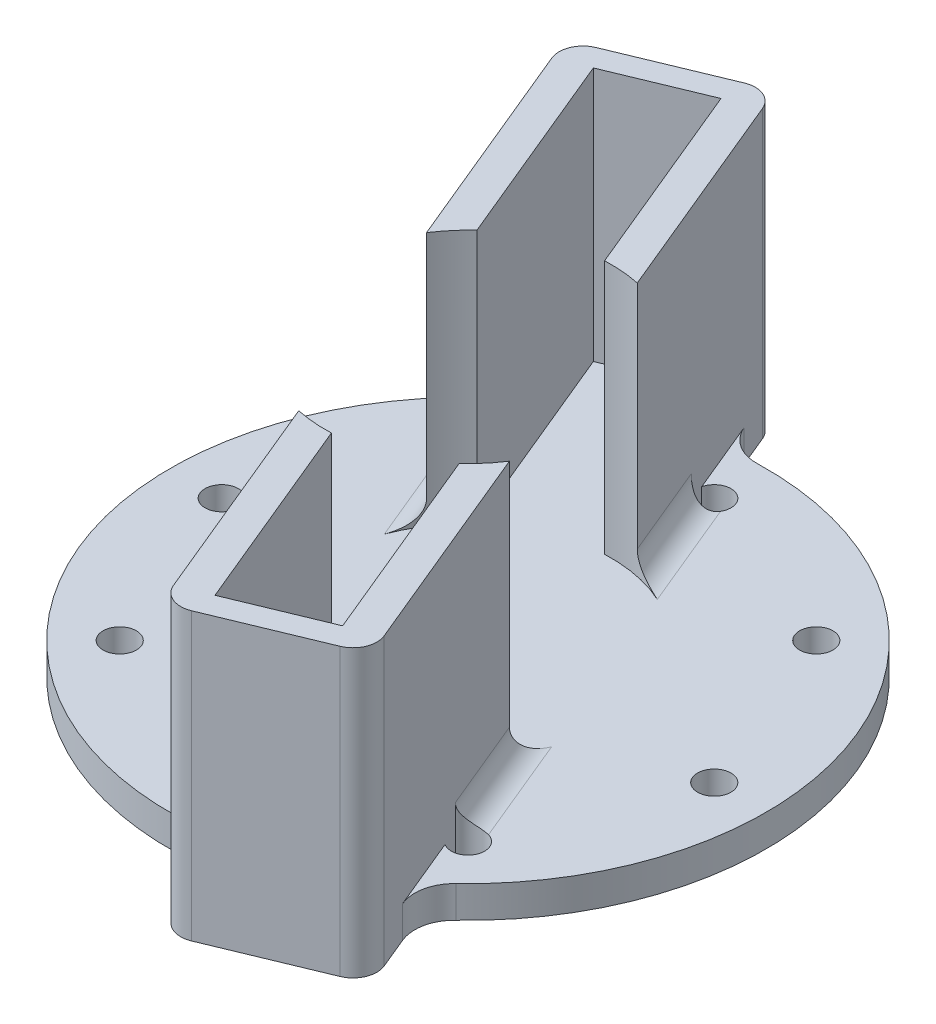
SolidWorks part; units mm, degrees
ref_plane "Alzado" through (0, 0, 0) normal (0, 0, 1) x (1, 0, 0)
ref_plane "Planta" through (0, 0, 0) normal (0, 1, 0) x (1, 0, 0)
ref_plane "Vista lateral" through (0, 0, 0) normal (1, 0, 0) x (0, 0, -1)
sketch "Croquis2" plane through (0, 0, 0) normal (0, 1, 0) x (1, 0, 0)
  circle A0 centre (0, 0) radius 37.5
  dimension "D1" = 75
extrude "Saliente-Extruir1" add sketch "Croquis2" along normal blind 4
sketch "Croquis3" plane through (0, 4, 0) normal (0, 1, 0) x (1, 0, 0)
  circle A0 centre (0, 31) radius 2.1
  circle A1 centre (21.9203, 21.9203) radius 2.1
  circle A2 centre (31, 0) radius 2.1
  circle A3 centre (21.9203, -21.9203) radius 2.1
  circle A4 centre (0, -31) radius 2.1
  circle A5 centre (-21.9203, -21.9203) radius 2.1
  circle A6 centre (-31, 0) radius 2.1
  circle A7 centre (-21.9203, 21.9203) radius 2.1
  circle A8 centre (0, 0) radius 31 construction
  point P4 (0, 0)
  point P20 (-1.7464, -34.9192)
  dimension "D1" = 4.2
  dimension "D2" = 31
  dimension "D3" = 8
extrude "Cortar-Extruir1" cut sketch "Croquis3" against normal blind 4
sketch "Croquis4" plane through (0, 4, 0) normal (0, 1, 0) x (1, 0, 0)
  line L0 (16.4554, -39.7268) -> (-16.4554, 39.7268)
  line L1 (0, 0) -> (0, 37.5) construction
  line L2 (0, 0) -> (-21.9203, 21.9203) construction
  line L3 (22.1372, -37.3733) -> (-10.7735, 42.0803)
  line L4 (10.7735, -42.0803) -> (-22.1372, 37.3733)
  line L5 (-10.7735, 42.0803) -> (-22.1372, 37.3733)
  line L6 (22.1372, -37.3733) -> (10.7735, -42.0803)
  circle A0 centre (0, 0) radius 37.5 construction
  point P4 (0, 0)
  point P15 (-22.1043, 37.3733)
  circle M11 centre (0, 0) radius 37.5
  dimension "D1" = 86
  dimension "D2" = 22.5
  dimension "D3" = 6.15
  dimension "D4" = 6.15
extrude "Saliente-Extruir2" add sketch "Croquis4" along normal blind 20 and the other way blind 4 contours L4 L0 M11 | L3 L0 M11 | L6 L0 L4 M11 | L6 L3 L0 M11 | L0 L5 L4 M11 | L3 L5 L0 M11
sketch "Croquis6" plane through (0, 4, 0) normal (0, 1, 0) x (1, 0, 0)
  line L4 (-22.1372, 37.3733) -> (10.7735, -42.0803)
  line L5 (10.7735, -42.0803) -> (22.1372, -37.3733)
  line L6 (22.1372, -37.3733) -> (-10.7735, 42.0803)
  line L7 (-10.7735, 42.0803) -> (-22.1372, 37.3733)
  line L8 (-22.1372, 37.3733) -> (10.7735, -42.0803)
  line L9 (10.7735, -42.0803) -> (22.1372, -37.3733)
  line L10 (22.1372, -37.3733) -> (-10.7735, 42.0803)
  line L11 (-10.7735, 42.0803) -> (-22.1372, 37.3733)
  line L16 (-27.3635, 39.5381) -> (8.6087, -47.3066)
  line L17 (8.6087, -47.3066) -> (27.3635, -39.5381)
  line L18 (27.3635, -39.5381) -> (-8.6087, 47.3066)
  line L19 (-8.6087, 47.3066) -> (-27.3635, 39.5381)
  line L20 (-27.3635, 39.5381) -> (8.6087, -47.3066)
  line L21 (8.6087, -47.3066) -> (27.3635, -39.5381)
  line L22 (27.3635, -39.5381) -> (-8.6087, 47.3066)
  line L23 (-8.6087, 47.3066) -> (-27.3635, 39.5381)
  dimension "D1" = 0
  dimension "D2" = 4
extrude "Saliente-Extruir3" add sketch "Croquis6" along normal blind 20 and the other way blind 4
sketch "Croquis8" plane through (0, 24, 0) normal (0, 1, 0) x (1, 0, 0)
  line L8 (-10.7735, 42.0803) -> (-22.1372, 37.3733)
  line L9 (-22.1372, 37.3733) -> (10.7735, -42.0803)
  line L10 (10.7735, -42.0803) -> (22.1372, -37.3733)
  line L11 (22.1372, -37.3733) -> (-10.7735, 42.0803)
  line L12 (-10.7735, 42.0803) -> (-22.1372, 37.3733)
  line L13 (-22.1372, 37.3733) -> (10.7735, -42.0803)
  line L14 (10.7735, -42.0803) -> (22.1372, -37.3733)
  line L15 (22.1372, -37.3733) -> (-10.7735, 42.0803)
  dimension "D1" = 4
extrude "Cortar-Extruir2" cut sketch "Croquis8" against normal up to vertex (20 mm away)
sketch "Croquis9" plane through (0, 24, 0) normal (0, 1, 0) x (1, 0, 0)
  circle A0 centre (0, 0) radius 18
  dimension "D1" = 36
extrude "Cortar-Extruir3" cut sketch "Croquis9" against normal up to vertex (20 mm away)
fillet "Redondeo1" radius 3 4 edges at (17.4694, 4, 15.6517) (1.2853, 4, -23.4202) (-1.2853, 4, 23.4202) (-17.4694, 4, -15.6517)
fillet "Redondeo2" radius 3 4 edges at (27.3635, 12, 39.5381) (-8.6087, 12, -47.3066) (8.6087, 12, 47.3066) (-27.3635, 12, -39.5381)
fillet "Redondeo3" radius 5 4 edges at (-23.1923, 2, -29.468) (4.4376, 2, 37.2365) (23.1923, 2, 29.468) (-4.4376, 2, -37.2365)
sketch "Croquis10" plane through (0, 24, 0) normal (0, 1, 0) x (1, 0, 0)
  line L0 (10.7735, -42.0803) -> (22.1372, -37.3733) construction
  line L2 (-10.7735, 42.0803) -> (-22.1372, 37.3733) construction
  line L3 (10.7735, -42.0803) -> (22.1372, -37.3733)
  line L4 (-10.7735, 42.0803) -> (-22.1372, 37.3733)
  line L33 (-11.1562, 43.0042) -> (-22.5199, 38.2972)
  line L34 (11.1562, -43.0042) -> (22.5199, -38.2972)
  line L35 (-10.7735, 42.0803) -> (-11.1562, 43.0042)
  line L36 (-22.5199, 38.2972) -> (-22.1372, 37.3733)
  line L37 (22.5199, -38.2972) -> (22.1372, -37.3733)
  line L38 (10.7735, -42.0803) -> (11.1562, -43.0042)
  point P8 (0, 0)
  point P10 (0, 0)
  point P11 (11.1562, -43.1081)
  dimension "D1" = 1
extrude "Cortar-Extruir4" cut sketch "Croquis10" against normal up to vertex (20 mm away)
sketch "Croquis11" plane through (0, 24, 0) normal (0, 1, 0) x (1, 0, 0)
  line L0 (22.5199, -38.2972) -> (11.1562, -43.0042) construction
  line L1 (11.1562, -43.0042) -> (0.7919, -17.9826) construction
  line L2 (-3.6887, -17.618) -> (7.4607, -44.5349) construction
  line L3 (11.3804, -46.1585) -> (24.5919, -40.6862) construction
  line L4 (26.2154, -36.7665) -> (15.0661, -9.8495) construction
  line L5 (12.1556, -13.2756) -> (22.5199, -38.2972) construction
  line L6 (-22.5199, 38.2972) -> (-11.1562, 43.0042) construction
  line L7 (-11.1562, 43.0042) -> (-0.7919, 17.9826) construction
  line L8 (3.6887, 17.618) -> (-7.4607, 44.5349) construction
  line L9 (-11.3804, 46.1585) -> (-24.5919, 40.6862) construction
  line L10 (-26.2154, 36.7665) -> (-15.0661, 9.8495) construction
  line L11 (-12.1556, 13.2756) -> (-22.5199, 38.2972) construction
  line L12 (22.5199, -38.2972) -> (11.1562, -43.0042)
  line L13 (11.1562, -43.0042) -> (0.7919, -17.9826)
  line L14 (-3.6887, -17.618) -> (7.4607, -44.5349)
  line L15 (11.3804, -46.1585) -> (24.5919, -40.6862)
  line L16 (26.2154, -36.7665) -> (15.0661, -9.8495)
  line L17 (12.1556, -13.2756) -> (22.5199, -38.2972)
  line L18 (-22.5199, 38.2972) -> (-11.1562, 43.0042)
  line L19 (-11.1562, 43.0042) -> (-0.7919, 17.9826)
  line L20 (3.6887, 17.618) -> (-7.4607, 44.5349)
  line L21 (-11.3804, 46.1585) -> (-24.5919, 40.6862)
  line L22 (-26.2154, 36.7665) -> (-15.0661, 9.8495)
  line L23 (-12.1556, 13.2756) -> (-22.5199, 38.2972)
  arc A0 (-3.6887, -17.618) -> (0.7919, -17.9826) centre (0, 0) ccw construction
  arc A1 (7.4607, -44.5349) -> (11.3804, -46.1585) centre (10.2323, -43.3869) ccw construction
  arc A2 (24.5919, -40.6862) -> (26.2154, -36.7665) centre (23.4438, -37.9145) ccw construction
  arc A3 (12.1556, -13.2756) -> (15.0661, -9.8495) centre (0, 0) ccw construction
  arc A4 (3.6887, 17.618) -> (-0.7919, 17.9826) centre (0, 0) ccw construction
  arc A5 (-7.4607, 44.5349) -> (-11.3804, 46.1585) centre (-10.2323, 43.3869) ccw construction
  arc A6 (-24.5919, 40.6862) -> (-26.2154, 36.7665) centre (-23.4438, 37.9145) ccw construction
  arc A7 (-12.1556, 13.2756) -> (-15.0661, 9.8495) centre (0, 0) ccw construction
  arc A8 (-3.6887, -17.618) -> (0.7919, -17.9826) centre (0, 0) ccw
  arc A9 (7.4607, -44.5349) -> (11.3804, -46.1585) centre (10.2323, -43.3869) ccw
  arc A10 (24.5919, -40.6862) -> (26.2154, -36.7665) centre (23.4438, -37.9145) ccw
  arc A11 (12.1556, -13.2756) -> (15.0661, -9.8495) centre (0, 0) ccw
  arc A12 (3.6887, 17.618) -> (-0.7919, 17.9826) centre (0, 0) ccw
  arc A13 (-7.4607, 44.5349) -> (-11.3804, 46.1585) centre (-10.2323, 43.3869) ccw
  arc A14 (-24.5919, 40.6862) -> (-26.2154, 36.7665) centre (-23.4438, 37.9145) ccw
  arc A15 (-12.1556, 13.2756) -> (-15.0661, 9.8495) centre (0, 0) ccw
extrude "Saliente-Extruir4" add sketch "Croquis11" along normal blind 12
